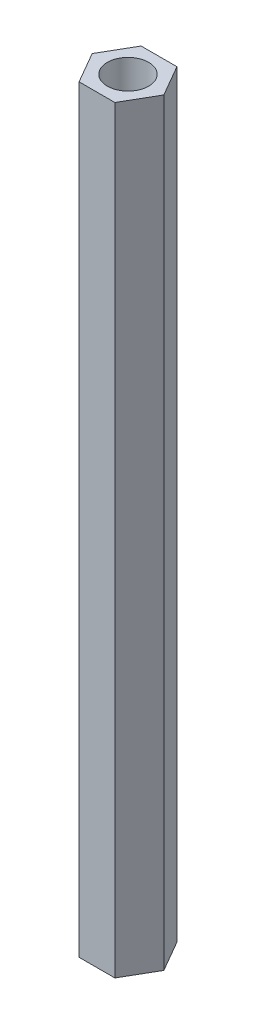
SolidWorks part; units mm, degrees
ref_plane "Front Plane" through (0, 0, 0) normal (0, 0, 1) x (1, 0, 0)
ref_plane "Top Plane" through (0, 0, 0) normal (0, 1, 0) x (1, 0, 0)
ref_plane "Right Plane" through (0, 0, 0) normal (1, 0, 0) x (0, 0, -1)
sketch "Sketch1" plane through (0, 0, 0) normal (0, 1, 0) x (1, 0, 0)
  line L1 (2.5981, 0) -> (1.299, 2.25)
  line L2 (1.299, 2.25) -> (-1.299, 2.25)
  line L3 (-1.299, 2.25) -> (-2.5981, 0)
  line L4 (-2.5981, 0) -> (-1.299, -2.25)
  line L5 (-1.299, -2.25) -> (1.299, -2.25)
  line L6 (1.299, -2.25) -> (2.5981, 0)
  circle A0 centre (0, 0) radius 2.25 construction
  circle A1 centre (0, 0) radius 1.5
  dimension "D1" = 4.5
  dimension "D2" = 3
extrude "Boss-Extrude1" add sketch "Sketch1" along normal blind 55
